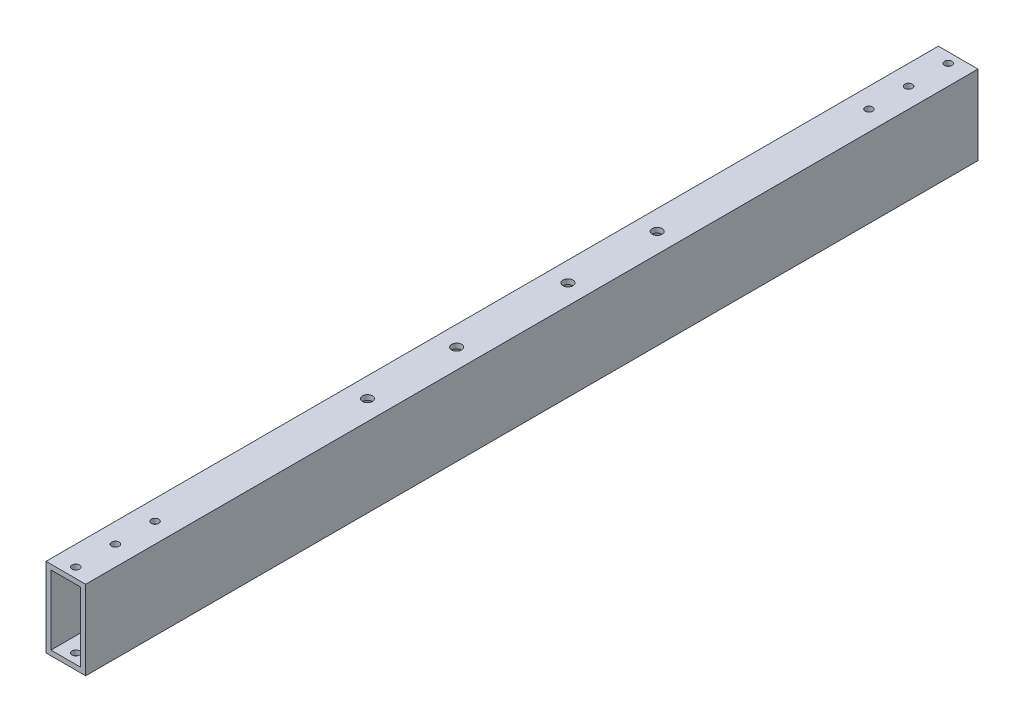
SolidWorks part; units mm, degrees
material "6061-T6 (SS)"
ref_plane "Front Plane" through (0, 0, 0) normal (0, 0, 1) x (1, 0, 0)
ref_plane "Top Plane" through (0, 0, 0) normal (0, 1, 0) x (1, 0, 0)
ref_plane "Right Plane" through (0, 0, 0) normal (1, 0, 0) x (0, 0, -1)
sketch "Sketch1" plane through (0, 0, 0) normal (0, 0, 1) x (1, 0, 0)
  line L1 (-12.7, -25.4) -> (12.7, -25.4)
  line L2 (-12.7, -25.4) -> (-12.7, 25.4)
  line L3 (-12.7, 25.4) -> (12.7, 25.4)
  line L4 (12.7, -25.4) -> (12.7, 25.4)
  line L5 (-12.7, -25.4) -> (12.7, 25.4) construction
  line L6 (-12.7, 25.4) -> (12.7, -25.4) construction
  point P0 (0, 0)
  dimension "D1" = 50.8
  dimension "D2" = 25.4
extrude "Extrude-Thin1" add sketch "Sketch1" along normal blind 571.5 thin thin type one direction reverse wall 3.175
hole_wizard "3/16 (0.1875) Diameter Hole1" positions "3DSketch1" profile "Sketch3" hole size "3/16" standard "ANSI Inch" end condition through all
sketch3d "3DSketch1"
  line L1 (12.7, 25.4, 0) -> (-12.7, 25.4, 0) construction
  line L6 (0, 25.4, 571.5) -> (0, 25.4, 0) construction
  line L7 (12.7, 25.4, 571.5) -> (-12.7, 25.4, 571.5) construction
  point P57 (0, 25.4, 6.35)
  point P59 (0, 25.4, 31.75)
  point P61 (0, 25.4, 57.15)
  point P63 (0, 25.4, 539.75)
  point P65 (0, 25.4, 514.35)
  point P67 (0, 25.4, 565.15)
  dimension "D1" = 25.4
  dimension "D2" = 25.4
  dimension "D3" = 6.35
  dimension "D4" = 25.4
  dimension "D5" = 25.4
  dimension "D6" = 6.35
sketch "Sketch3" plane through (0, 25.4, 565.15) normal (1, 0, 0) x (0, 0, 1)
  line L0 (0, 0) -> (0, 50.8)
  line L1 (0, 50.8) -> (2.3812, 50.8)
  line L2 (2.3812, 50.8) -> (2.3812, 0)
  line L5 (2.3812, 0) -> (0, 0)
  line L11 (0, -6.35) -> (0, 107.95) construction
  dimension "Thru Hole Dia." = 4.7625
  dimension "Thru Hole Depth" = 50.8
hole_wizard "1/4 (0.25) Diameter Hole1" positions "Sketch6" profile "Sketch7" hole size "1/4" standard "ANSI Inch" end condition through all
sketch "Sketch6" plane through (0, 25.4, 0) normal (0, 1, 0) x (1, 0, 0)
  point P0 (0, -321.183)
  point P3 (0, -378.333)
  point P6 (0, -192.786)
  point P9 (0, -249.936)
sketch "Sketch7" plane through (0, 25.4, 321.183) normal (1, 0, 0) x (0, 0, 1)
  line L0 (0, 0) -> (0, 50.8)
  line L1 (0, 50.8) -> (3.175, 50.8)
  line L2 (3.175, 50.8) -> (3.175, 0)
  line L5 (3.175, 0) -> (0, 0)
  line L11 (0, -6.35) -> (0, 107.95) construction
  dimension "Thru Hole Dia." = 6.35
  dimension "Thru Hole Depth" = 50.8
hole_wizard "E (0.25) Diameter Hole1" positions "Sketch8" profile "Sketch9" hole size "E" standard "ANSI Inch"
sketch "Sketch8" plane through (-12.7, 0, 0) normal (-1, 0, 0) x (0, 0, 1)
  point P0 (103.886, 17.145)
  point P3 (103.886, 1.27)
  point P6 (116.586, 8.89)
  point P13 (454.914, 8.89)
  point P16 (467.614, 1.27)
  point P19 (467.614, 17.145)
sketch "Sketch9" plane through (-12.7, 17.145, 103.886) normal (0, 1, 0) x (0, 0, 1)
  line L0 (0, 0) -> (0, 8.2577)
  line L1 (0, 8.2577) -> (3.175, 6.35)
  line L2 (3.175, 6.35) -> (3.175, 0)
  line L5 (3.175, 0) -> (0, 0)
  line L10 (0, 8.2577) -> (-3.175, 6.35) construction
  line L11 (0, -6.35) -> (0, 107.95) construction
  dimension "Hole Dia." = 6.35
  dimension "Hole Depth" = 6.35
  dimension "Drill Angle" = 118
